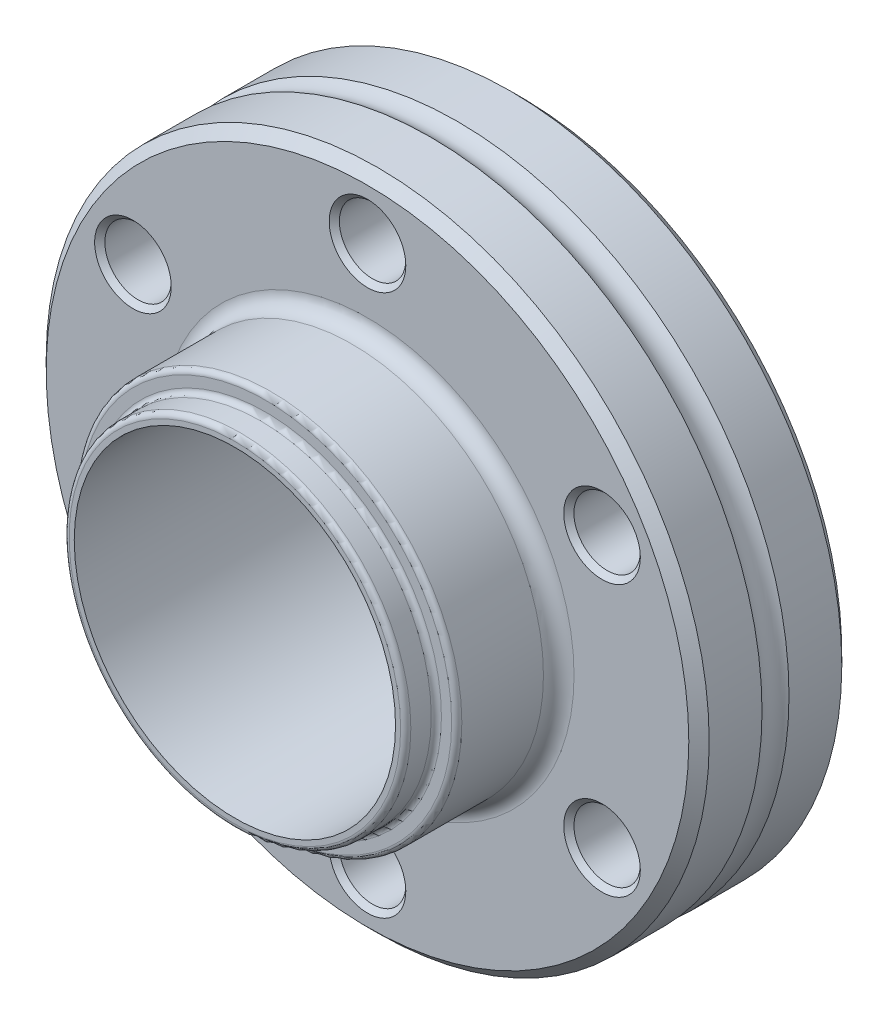
SolidWorks part; units mm, degrees
material "AISI 304"
ref_plane "Front Plane" through (0, 0, 0) normal (0, 0, 1) x (1, 0, 0)
ref_plane "Top Plane" through (0, 0, 0) normal (0, 1, 0) x (1, 0, 0)
ref_plane "Right Plane" through (0, 0, 0) normal (1, 0, 0) x (0, 0, -1)
sketch "Sketch1" plane through (0, 0, 0) normal (0, 1, 0) x (1, 0, 0)
  line L0 (9.0861, 5.9436) -> (0, 5.9436)
  line L1 (0, 5.9436) -> (0, -0.508)
  line L2 (0, -0.508) -> (16.51, -0.508)
  line L3 (16.51, -0.508) -> (16.51, 2.63)
  line L4 (16.51, 3.974) -> (16.51, 7.112)
  line L5 (16.51, 7.112) -> (10.7315, 7.112)
  line L6 (10.7315, 7.112) -> (10.7315, 5.92)
  line L7 (10.7315, 5.92) -> (9.271, 6.4516)
  line L8 (9.271, 6.4516) -> (9.0861, 5.9436)
  line L9 (0, 7.112) -> (0, -0.508) construction
  arc A0 (16.51, 2.63) -> (16.51, 3.974) centre (17.272, 3.302) cw
revolve "Revolve1" add sketch "Sketch1" angle 360 about L9
sketch "Sketch2" plane through (0, 0, 0.508) normal (0, 0, 1) x (1, 0, 0)
  circle A0 centre (0, 0) radius 9.525
extrude "Boss-Extrude1" add sketch "Sketch2" along normal blind 5.08
sketch "Sketch3" plane through (0, 0, 5.588) normal (0, 0, 1) x (1, 0, 0)
  circle A0 centre (0, 0) radius 8.509
extrude "Boss-Extrude2" add sketch "Sketch3" along normal blind 1.524
hole_wizard "Hole1" positions "Sketch5" profile "Sketch4" legacy
sketch "Sketch5" plane through (0, 0, 7.112) normal (0, 0, 1) x (1, 0, 0)
  point P0 (0, 0)
sketch "Sketch4" plane through (0, 0, 7.112) normal (1, 0, 0) x (0, -1, 0)
  line L0 (0, 0) -> (0, 14.224)
  line L1 (0, 14.224) -> (8.001, 14.224)
  line L2 (8.001, 14.224) -> (8.001, 0)
  line L3 (8.001, 0) -> (0, 0)
  line L4 (0, 110) -> (0, -10) construction
  dimension "Diameter" = 16.002
  dimension "Depth" = 14.224
hole_wizard "#4 Clearance Hole1" positions "Sketch7" profile "Sketch6" hole size "#4" standard "ANSI Inch"
sketch "Sketch7" plane through (0, 0, 0.508) normal (0, 0, 1) x (1, 0, 0)
  point P0 (11.6804, -6.7437)
sketch "Sketch6" plane through (11.6804, -6.7437, 0.508) normal (1, 0, 0) x (0, -1, 0)
  line L0 (0, 0) -> (0, 7.62)
  line L1 (0, 7.62) -> (1.6535, 7.62)
  line L2 (1.6535, 7.62) -> (1.6535, 0)
  line L5 (1.6535, 0) -> (0, 0)
  line L11 (0, -6.35) -> (0, 107.95) construction
  dimension "Thru Hole Dia." = 3.3071
  dimension "Thru Hole Depth" = 7.62
hole_wizard "#4 Clearance Hole2" positions "Sketch9" profile "Sketch8" hole size "#4" standard "ANSI Inch"
sketch "Sketch9" plane through (0, 0, -7.112) normal (0, 0, -1) x (-1, 0, 0)
  point P0 (0, 13.4874)
  point P1 (11.6804, 6.7437)
  point P2 (11.6804, -6.7437)
  point P3 (0, -13.4874)
  point P4 (-11.6804, 6.7437)
sketch "Sketch8" plane through (0, 13.4874, -7.112) normal (1, 0, 0) x (0, 1, 0)
  line L0 (0, 0) -> (0, 14.224)
  line L1 (0, 14.224) -> (1.6535, 14.224)
  line L2 (1.6535, 14.224) -> (1.6535, 0)
  line L5 (1.6535, 0) -> (0, 0)
  line L11 (0, -6.35) -> (0, 107.95) construction
  dimension "Thru Hole Dia." = 3.3071
  dimension "Thru Hole Depth" = 14.224
chamfer "Chamfer1" distance 0.254 angle 45 12 edges at (13.334, -6.7437, -7.112) (1.6535, -13.4874, 0.508) (-10.0269, 6.7437, 0.508) (13.334, 6.7437, 0.508) (-1.6535, -13.4874, -7.112) (10.0269, 6.7437, -7.112) (1.6535, 13.4874, 0.508) (-10.0269, -6.7437, 0.508) (13.334, -6.7437, 0.508) (-13.334, -6.7437, -7.112) (-1.6535, 13.4874, -7.112) (-13.334, 6.7437, -7.112)
chamfer "Chamfer2" distance 0.508 angle 45 2 edges at (16.51, 0, -7.112) (16.51, 0, 0.508)
fillet "Fillet1" radius 0.254 4 edges at (9.525, 0, 5.588) (8.509, 0, 5.588) (8.509, 0, 7.112) (-8.001, 0, -5.9436)
fillet "Fillet2" radius 0.762 1 edges at (9.525, 0, 0.508)
